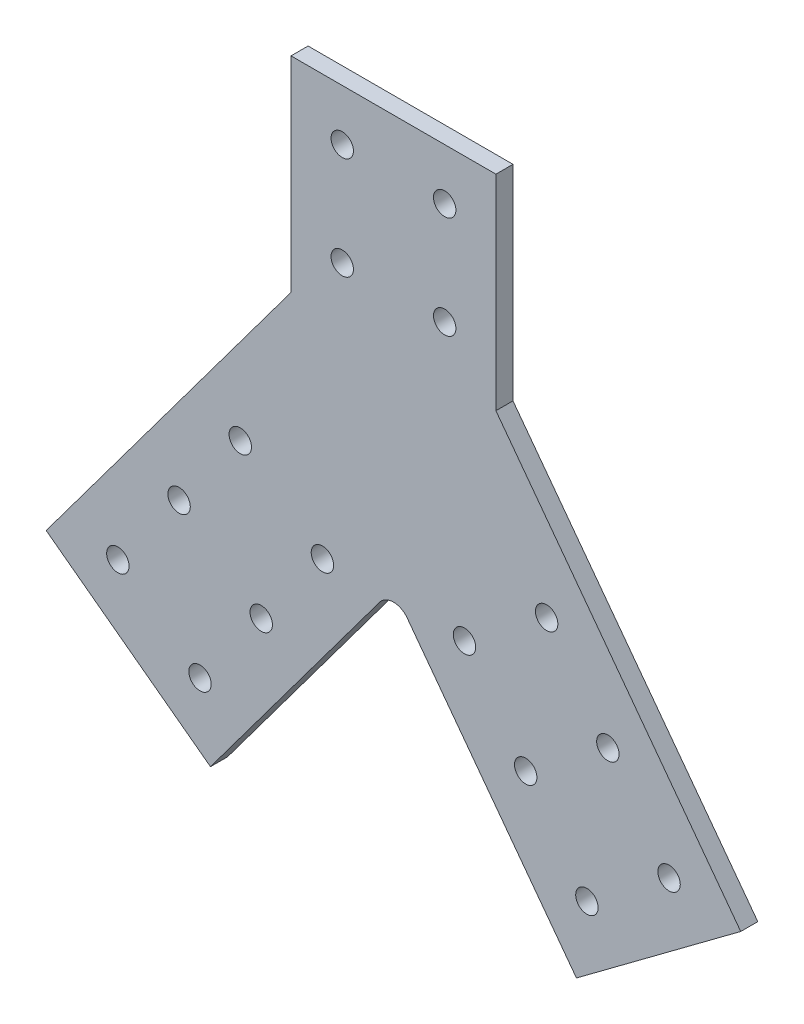
SolidWorks part; units mm, degrees
material "6061-T6 (SS)"
ref_plane "Front" through (0, 0, 0) normal (0, 0, 1) x (1, 0, 0)
ref_plane "Top" through (0, 0, 0) normal (0, 1, 0) x (1, 0, 0)
ref_plane "Right" through (0, 0, 0) normal (1, 0, 0) x (0, 0, -1)
sketch "Sketch1" plane through (0, 0, 0) normal (0, 0, 1) x (1, 0, 0)
  line L0 (0, 0) -> (76.2, 0)
  line L1 (76.2, 0) -> (76.2, -76.2)
  line L2 (76.2, -76.2) -> (167.2567, -198.4065)
  line L3 (167.2567, -198.4065) -> (106.1535, -243.9349)
  line L4 (106.1535, -243.9349) -> (38.1, -152.6008)
  line L5 (38.1, -152.6008) -> (-29.9535, -243.9349)
  line L6 (-29.9535, -243.9349) -> (-91.0567, -198.4065)
  line L7 (-91.0567, -198.4065) -> (0, -76.2)
  line L8 (0, -76.2) -> (0, 0)
  dimension "D1" = 76.2
  dimension "D2" = 76.2
  dimension "D3" = 76.2
  dimension "D4" = 143.31
  dimension "D5" = 143.31
  dimension "D6" = 76.2
  dimension "D7" = 76.2
  dimension "D8" = 152.4
  dimension "D9" = 152.4
extrude "Boss-Extrude1" add sketch "Sketch1" along normal blind 6.35
hole_wizard "21/64 (0.32813) Diameter Hole1" positions "Sketch2" profile "Sketch3" hole size "21/64" standard "ANSI Inch" end condition through all
sketch "Sketch2" plane through (0, 0, 6.35) normal (0, 0, 1) x (1, 0, 0)
  line L0 (76.2, -76.2) -> (76.2, 0) construction
  line L1 (76.2, 0) -> (0, 0) construction
  point P0 (57.15, -19.05)
  dimension "D1" = 19.05
  dimension "D2" = 19.05
sketch "Sketch3" plane through (57.15, -19.05, 6.35) normal (1, 0, 0) x (0, -1, 0)
  line L0 (0, 0) -> (0, 6.35)
  line L1 (0, 6.35) -> (4.1673, 6.35)
  line L2 (4.1673, 6.35) -> (4.1673, 0)
  line L5 (4.1673, 0) -> (0, 0)
  line L11 (0, -6.35) -> (0, 107.95) construction
  dimension "Thru Hole Dia." = 8.3345
  dimension "Thru Hole Depth" = 6.35
pattern_linear "LPattern1" count 2 spacing 38.1 along (-1, 0, 0) count 2 spacing 38.1 along (0, -1, 0) of "21/64 (0.32813) Diameter Hole1"
hole_wizard "21/64 (0.32813) Diameter Hole2" positions "Sketch4" profile "Sketch5" hole size "21/64" standard "ANSI Inch" end condition through all
sketch "Sketch4" plane through (0, 0, 6.35) normal (0, 0, 1) x (1, 0, 0)
  line L0 (0, -76.2) -> (-91.0567, -198.4065) construction
  line L1 (-91.0567, -198.4065) -> (-29.9535, -243.9349) construction
  point P0 (-64.3988, -194.5128)
  dimension "D1" = 19.05
  dimension "D2" = 19.05
sketch "Sketch5" plane through (-64.3988, -194.5128, 6.35) normal (1, 0, 0) x (0, -1, 0)
  line L0 (0, 0) -> (0, 6.35)
  line L1 (0, 6.35) -> (4.1673, 6.35)
  line L2 (4.1673, 6.35) -> (4.1673, 0)
  line L5 (4.1673, 0) -> (0, 0)
  line L11 (0, -6.35) -> (0, 107.95) construction
  dimension "Thru Hole Dia." = 8.3345
  dimension "Thru Hole Depth" = 6.35
pattern_linear "LPattern2" count 2 spacing 38.1 along (0.8019, -0.5975, 0) count 3 spacing 38.1 along (0.5975, 0.8019, 0) of "21/64 (0.32813) Diameter Hole2"
hole_wizard "21/64 (0.32813) Diameter Hole3" positions "Sketch6" profile "Sketch7" hole size "21/64" standard "ANSI Inch" end condition through all
sketch "Sketch6" plane through (0, 0, 6.35) normal (0, 0, 1) x (1, 0, 0)
  line L0 (167.2567, -198.4065) -> (76.2, -76.2) construction
  line L1 (106.1535, -243.9349) -> (167.2567, -198.4065) construction
  point P0 (140.5988, -194.5128)
  dimension "D1" = 19.05
  dimension "D2" = 19.05
sketch "Sketch7" plane through (140.5988, -194.5128, 6.35) normal (1, 0, 0) x (0, -1, 0)
  line L0 (0, 0) -> (0, 6.35)
  line L1 (0, 6.35) -> (4.1673, 6.35)
  line L2 (4.1673, 6.35) -> (4.1673, 0)
  line L5 (4.1673, 0) -> (0, 0)
  line L11 (0, -6.35) -> (0, 107.95) construction
  dimension "Thru Hole Dia." = 8.3345
  dimension "Thru Hole Depth" = 6.35
pattern_linear "LPattern3" count 2 spacing 38.1 along (-0.8019, -0.5975, 0) count 3 spacing 38.1 along (-0.5975, 0.8019, 0) of "21/64 (0.32813) Diameter Hole3"
fillet "Fillet1" radius 6.35 1 edges at (38.1, -152.6008, 3.175)
fillet "Fillet2" [suppressed] radius 6.35
